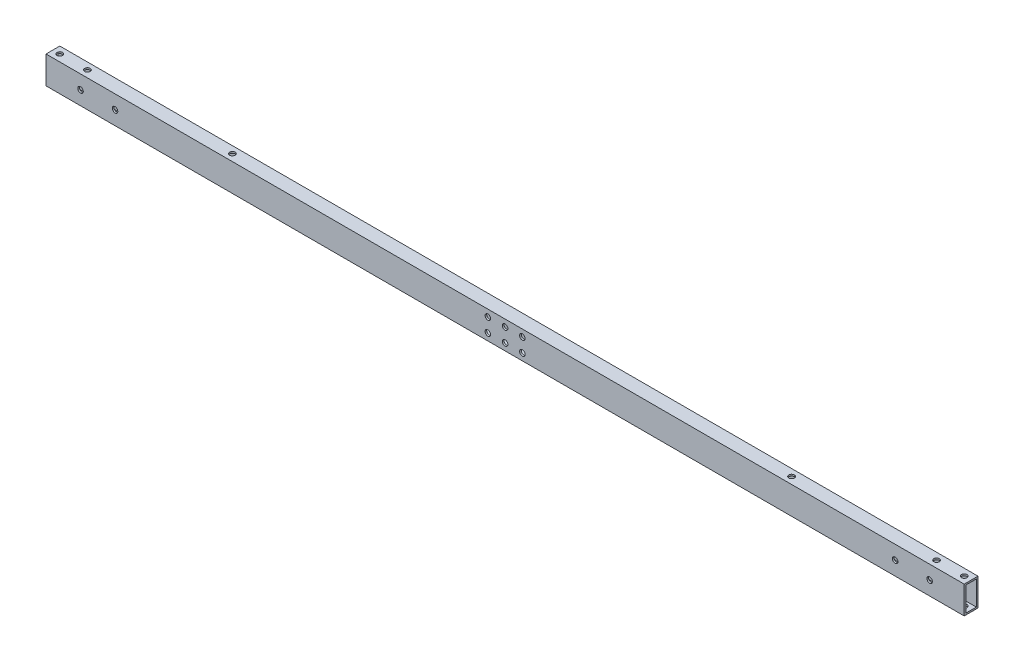
SolidWorks part; units mm, degrees
material "5052-H34"
ref_plane "正面" through (0, 0, 0) normal (0, 0, 1) x (1, 0, 0)
ref_plane "平面" through (0, 0, 0) normal (0, 1, 0) x (1, 0, 0)
ref_plane "右側面" through (0, 0, 0) normal (1, 0, 0) x (0, 0, -1)
sketch "ｽｹｯﾁ1" plane through (0, 0, 0) normal (1, 0, 0) x (0, 0, -1)
  line L1 (-5, 10) -> (5, 10)
  line L2 (-5, 10) -> (-5, -10)
  line L3 (-5, -10) -> (5, -10)
  line L4 (5, 10) -> (5, -10)
  line L5 (-5, 10) -> (5, -10) construction
  line L6 (-5, -10) -> (5, 10) construction
  point P0 (0, 0)
  dimension "D1" = 10
  dimension "D2" = 20
extrude "押し出し-薄板1" add sketch "ｽｹｯﾁ1" along normal blind 665 thin
sketch "ｽｹｯﾁ2" plane through (0, 0, 5) normal (0, 0, 1) x (1, 0, 0)
  line L0 (332.5, 10) -> (332.5, -10) construction
  line L1 (665, 10) -> (0, 10) construction
  line L2 (665, -10) -> (0, -10) construction
  line L3 (320, 0) -> (368, 0) construction
  line L4 (25, 0) -> (50, 0) construction
  line L5 (0, 0) -> (25, 0) construction
  line L6 (320, 5) -> (320, -5) construction
  line L7 (320, 5) -> (332.5, 5) construction
  circle A6 centre (25, 0) radius 2
  circle A7 centre (640, 0) radius 2
  circle A8 centre (50, 0) radius 2
  circle A9 centre (615, 0) radius 2
  circle A10 centre (320, 5) radius 2
  circle A11 centre (320, -5) radius 2
  circle A12 centre (345, -5) radius 2
  circle A13 centre (345, 5) radius 2
  circle A14 centre (332.5, 5) radius 2
  circle A15 centre (332.5, -5) radius 2
  dimension "D1" = 25
  dimension "D4" = 4
  dimension "D6" = 10
  dimension "D2" = 4
  dimension "D3" = 25
  dimension "D5" = 25
extrude "ｶｯﾄ - 押し出し1" cut sketch "ｽｹｯﾁ2" against normal through all
sketch "ｽｹｯﾁ3" plane through (0, 10, 0) normal (0, 1, 0) x (1, 0, 0)
  line L0 (332.5, 5) -> (332.5, -5) construction
  line L1 (665, 5) -> (0, 5) construction
  line L2 (665, -5) -> (0, -5) construction
  line L3 (0, 0) -> (130, 0) construction
  line L4 (665, 0) -> (535, 0) construction
  circle A0 centre (5, 0) radius 2
  circle A1 centre (130, 0) radius 2
  circle A2 centre (535, 0) radius 2
  circle A3 centre (660, 0) radius 2
  circle A4 centre (25, 0) radius 2
  circle A5 centre (640, 0) radius 2
  dimension "D1" = 4
  dimension "D2" = 5
  dimension "D3" = 125
  dimension "D4" = 20
extrude "ｶｯﾄ - 押し出し2" cut sketch "ｽｹｯﾁ3" against normal through all
